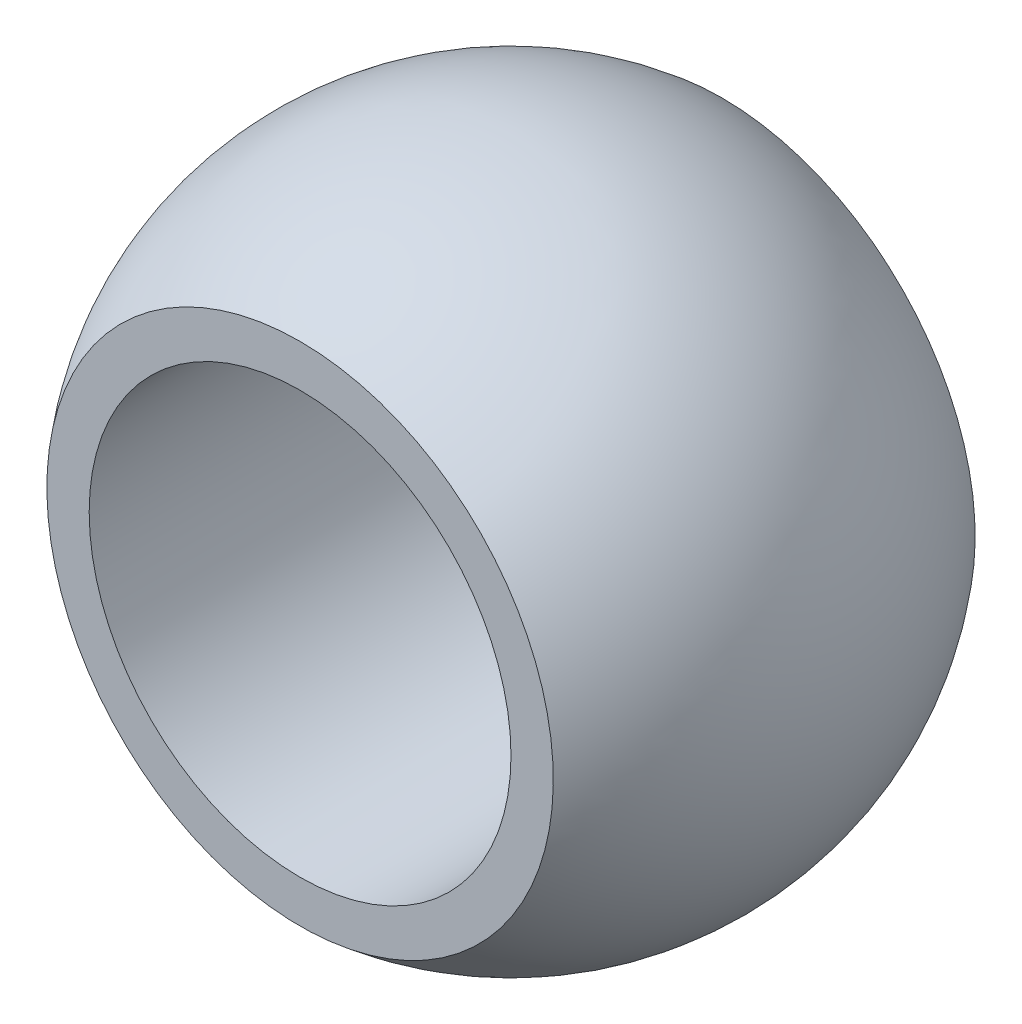
SolidWorks part; units mm, degrees
ref_plane "Front Plane" through (0, 0, 0) normal (0, 0, 1) x (1, 0, 0)
ref_plane "Top Plane" through (0, 0, 0) normal (0, 1, 0) x (1, 0, 0)
ref_plane "Right Plane" through (0, 0, 0) normal (1, 0, 0) x (0, 0, -1)
sketch "Sketch2" plane through (0, 0, 0) normal (1, 0, 0) x (0, 0, -1)
  line L0 (-4, 0) -> (0, 0) construction
  line L1 (0, 0) -> (4, 0) construction
  line L2 (0, 0) -> (0, 6.25) construction
  line L3 (-4, 4) -> (4, 4)
  line L4 (-4, 4.8023) -> (-4, 4)
  line L5 (4, 4.8023) -> (4, 4)
  arc A1 (4, 4.8023) -> (-4, 4.8023) centre (0, 0) ccw
  point P13 (0, 4)
  dimension "D1" = 6.25
  dimension "D2" = 8
  dimension "D3" = 8
revolve "Revolve1" add sketch "Sketch2" angle 360 about L0
